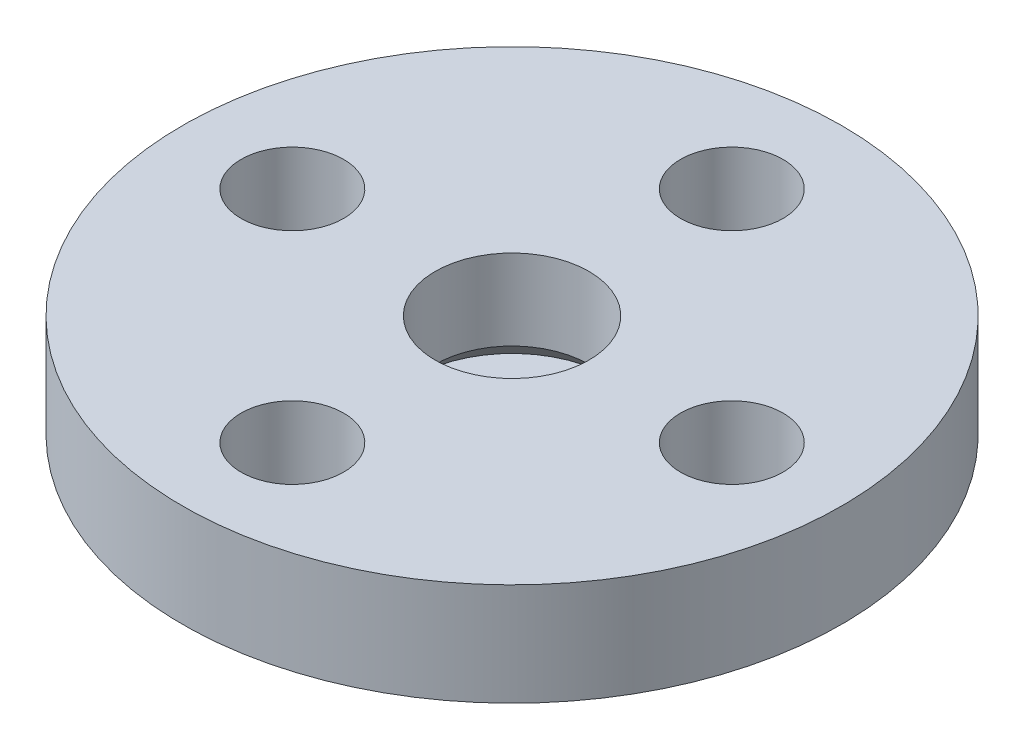
SolidWorks part; units mm, degrees
ref_plane "前视基准面" through (0, 0, 0) normal (0, 0, 1) x (1, 0, 0)
ref_plane "上视基准面" through (0, 0, 0) normal (0, 1, 0) x (1, 0, 0)
ref_plane "右视基准面" through (0, 0, 0) normal (1, 0, 0) x (0, 0, -1)
sketch "草图1" plane through (0, 0, 0) normal (1, 0, 0) x (0, 0, -1)
  line L0 (10.5, 14) -> (10.5, 3)
  line L1 (10.5, 3) -> (13.5, 0)
  line L2 (13.5, 0) -> (9, 0)
  line L3 (9, 0) -> (9, -12)
  line L4 (9, -12) -> (20, -12)
  line L5 (20, -12) -> (20, 0)
  line L6 (20, 0) -> (45, 0)
  line L7 (45, 0) -> (45, 14)
  line L8 (45, 14) -> (10.5, 14)
  line L9 (0, 0) -> (0, 78.4635) construction
  line L10 (9, 0) -> (8.6, 0) construction
  line L11 (8.6, 0) -> (8.6, 102.2657) construction
  line L12 (30, 0) -> (30, 14) construction
  line L13 (37, 0) -> (37, 14) construction
  line L14 (9, -7.5) -> (12, -7.5)
  line L15 (12, -7.5) -> (12, -12)
  line L17 (12, -7.5) -> (20, -7.5) construction
  dimension "D1" = 45
  dimension "B1" = 18
  dimension "A" = 17.2
  dimension "B" = 21
  dimension "C" = 14
  dimension "F" = 12
  dimension "E" = 3
  dimension "(d)" = 40
  dimension "L" = 14
  dimension "K" = 60
  dimension "D" = 90
  dimension "f2" = 4.5
  dimension "W" = 24
sketch "草图2" plane through (0, 0, 0) normal (1, 0, 0) x (0, 0, -1)
  line L1 (9, 0) -> (9, -12) construction
  line L2 (13.5, 0) -> (9, 0) construction
  line L3 (10.5, 3) -> (13.5, 0) construction
  line L4 (10.5, 14) -> (10.5, 3) construction
  line L5 (45, 14) -> (10.5, 14) construction
  line L6 (45, 0) -> (45, 14) construction
  line L7 (20, 0) -> (45, 0) construction
  line L8 (20, -12) -> (20, 0) construction
  line L9 (12, -12) -> (20, -12)
  line L10 (9, 0) -> (9, -7.5)
  line L11 (13.5, 0) -> (9, 0)
  line L12 (10.5, 3) -> (13.5, 0)
  line L13 (10.5, 14) -> (10.5, 3)
  line L14 (45, 14) -> (10.5, 14)
  line L15 (45, 0) -> (45, 14)
  line L16 (20, 0) -> (45, 0)
  line L17 (20, -7.5) -> (20, 0)
  line L18 (0, 0) -> (0, 34.0483) construction
  line L19 (0, 0) -> (0, 78.4635) construction
  line L20 (9, -7.5) -> (12, -7.5)
  line L21 (12, -7.5) -> (12, -12)
  line L22 (20, -12) -> (20, -7.5)
revolve "旋转1" add sketch "草图2" angle 360 about L18
sketch "草图3" plane through (0, 0, 0) normal (0, 1, 0) x (1, 0, 0)
  line L0 (0, 20) -> (0, 45) construction
  circle A0 centre (0, 30) radius 7
extrude "切除-拉伸1" cut sketch "草图3" along normal up to vertex (14 mm away) up to point (0, 14, -45)
pattern_circular "阵列(圆周)1" count 4 over 360 about axis through (0, 0, 0) along (0, 1, 0) of "切除-拉伸1"
